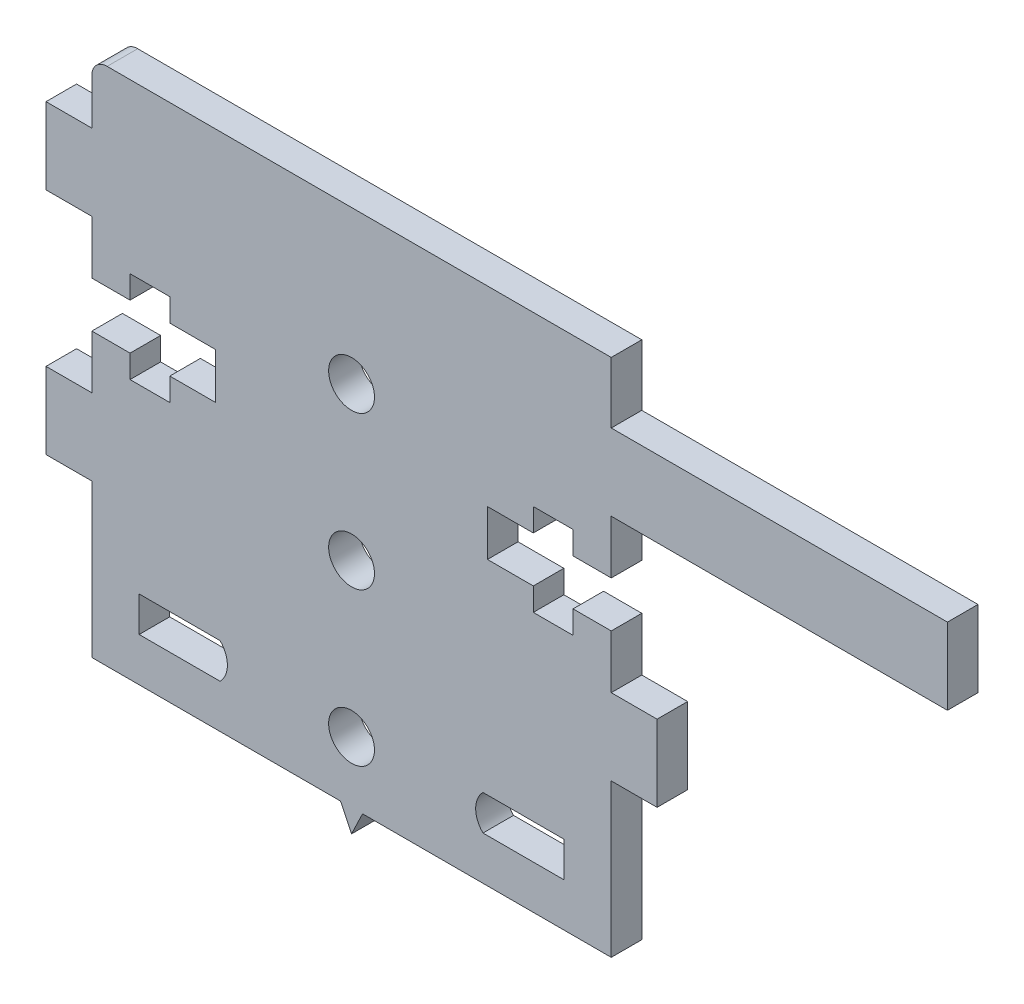
SolidWorks part; units mm, degrees
ref_plane "前视基准面" through (0, 0, 0) normal (0, 0, 1) x (1, 0, 0)
ref_plane "上视基准面" through (0, 0, 0) normal (0, 1, 0) x (1, 0, 0)
ref_plane "右视基准面" through (0, 0, 0) normal (1, 0, 0) x (0, 0, -1)
sketch "草图1" plane through (0, 0, 0) normal (0, 0, 1) x (1, 0, 0)
  line L25 (0, 0) -> (0, -5.483) construction
  line L26 (13.9, -11.15) -> (8.6, -11.15)
  line L27 (13.9, -8.85) -> (13.9, -11.15)
  line L34 (13.9, -8.85) -> (8.6, -8.85)
  line L35 (16.9939, 16) -> (16.9939, 20)
  line L36 (38.9939, 16) -> (16.9939, 16)
  line L37 (38.9939, 11) -> (38.9939, 16)
  line L38 (16.9939, 11) -> (38.9939, 11)
  line L40 (19.9939, -4) -> (16.9939, -4)
  line L41 (19.9939, 1) -> (16.9939, 1)
  line L42 (19.9939, -4) -> (19.9939, 1)
  line L47 (0, 0) -> (0, 10) construction
  line L64 (0, -14) -> (0, -15.5)
  line L65 (-19.9939, -4) -> (-19.9939, 1)
  line L66 (-19.9939, 1) -> (-16.9939, 1)
  line L71 (-19.9939, -4) -> (-16.9939, -4)
  line L77 (-13.9, -8.85) -> (-8.6, -8.85)
  line L78 (-13.9, -8.85) -> (-13.9, -11.15)
  line L79 (-13.9, -11.15) -> (-8.6, -11.15)
  line L84 (16.9939, -4) -> (16.9939, -13)
  line L87 (-16.9939, -13) -> (-16.9939, -4)
  line L92 (16.9939, -13) -> (16.9939, -14)
  line L93 (-16.9939, -14) -> (-16.9939, -13)
  line L94 (0, -15.5) -> (0.7212, -14)
  line L95 (0.7212, -14) -> (16.9939, -14)
  line L96 (-0.7212, -14) -> (-16.9939, -14)
  line L97 (0, -15.5) -> (-0.7212, -14)
  line L98 (-14.4939, 4.5) -> (-14.4939, 3)
  line L99 (-8.8939, 7.5) -> (-8.8939, 4.5)
  line L100 (-14.4939, 7.5) -> (-14.4939, 9)
  line L101 (-16.9939, 7.5) -> (-14.4939, 7.5)
  line L102 (-14.4939, 3) -> (-11.8939, 3)
  line L103 (-11.8939, 3) -> (-11.8939, 4.5)
  line L104 (-11.8939, 4.5) -> (-8.8939, 4.5)
  line L105 (-11.8939, 7.5) -> (-8.8939, 7.5)
  line L106 (-11.8939, 9) -> (-11.8939, 7.5)
  line L107 (-14.4939, 9) -> (-11.8939, 9)
  line L108 (-14.4939, 4.5) -> (-16.9939, 4.5)
  line L109 (-16.9939, 11) -> (-16.9939, 7.5)
  line L110 (-16.9939, 4.5) -> (-16.9939, 1)
  line L111 (-16.9939, 16) -> (-16.9939, 19)
  line L112 (-15.9939, 20) -> (16.9939, 20)
  line L113 (-16.9939, 11) -> (-19.9939, 11)
  line L114 (-19.9939, 11) -> (-19.9939, 16)
  line L115 (-19.9939, 16) -> (-16.9939, 16)
  line L124 (16.9939, 4.5) -> (16.9939, 1)
  line L125 (16.9939, 11) -> (16.9939, 7.5)
  line L126 (14.4939, 4.5) -> (16.9939, 4.5)
  line L127 (14.4939, 9) -> (11.8939, 9)
  line L128 (11.8939, 9) -> (11.8939, 7.5)
  line L129 (11.8939, 7.5) -> (8.8939, 7.5)
  line L130 (11.8939, 4.5) -> (8.8939, 4.5)
  line L131 (11.8939, 3) -> (11.8939, 4.5)
  line L132 (14.4939, 3) -> (11.8939, 3)
  line L133 (16.9939, 7.5) -> (14.4939, 7.5)
  line L134 (14.4939, 7.5) -> (14.4939, 9)
  line L135 (8.8939, 7.5) -> (8.8939, 4.5)
  line L136 (14.4939, 4.5) -> (14.4939, 3)
  circle A4 centre (0, -10) radius 1.5
  circle A6 centre (0, 0) radius 1.5
  circle A7 centre (0, 10) radius 1.5
  arc A8 (-8.6, -8.85) -> (-8.6, -11.15) centre (-9.75, -10) cw
  arc A9 (8.6, -8.85) -> (8.6, -11.15) centre (9.75, -10) ccw
  arc A11 (-15.9939, 20) -> (-16.9939, 19) centre (-15.9939, 19) ccw
  dimension "D1" = 1
extrude "凸台-拉伸1" add sketch "草图1" along normal blind 2
sketch "草图2" plane through (-16.9939, 0, 0) normal (-1, 0, 0) x (0, 0, 1)
  line L0 (1, 7.5) -> (1, 4.5)
  line L1 (2, 7.5) -> (0, 7.5) construction
  line L2 (2, 4.5) -> (0, 4.5) construction
  circle A0 centre (1, 6) radius 1.5
sketch "草图3" plane through (16.9939, 0, 0) normal (1, 0, 0) x (0, 0, -1)
  line L0 (-1, 7.5) -> (-1, 4.5)
  line L1 (-2, 7.5) -> (0, 7.5) construction
  line L2 (-2, 4.5) -> (0, 4.5) construction
  circle A0 centre (-1, 6) radius 1.5
